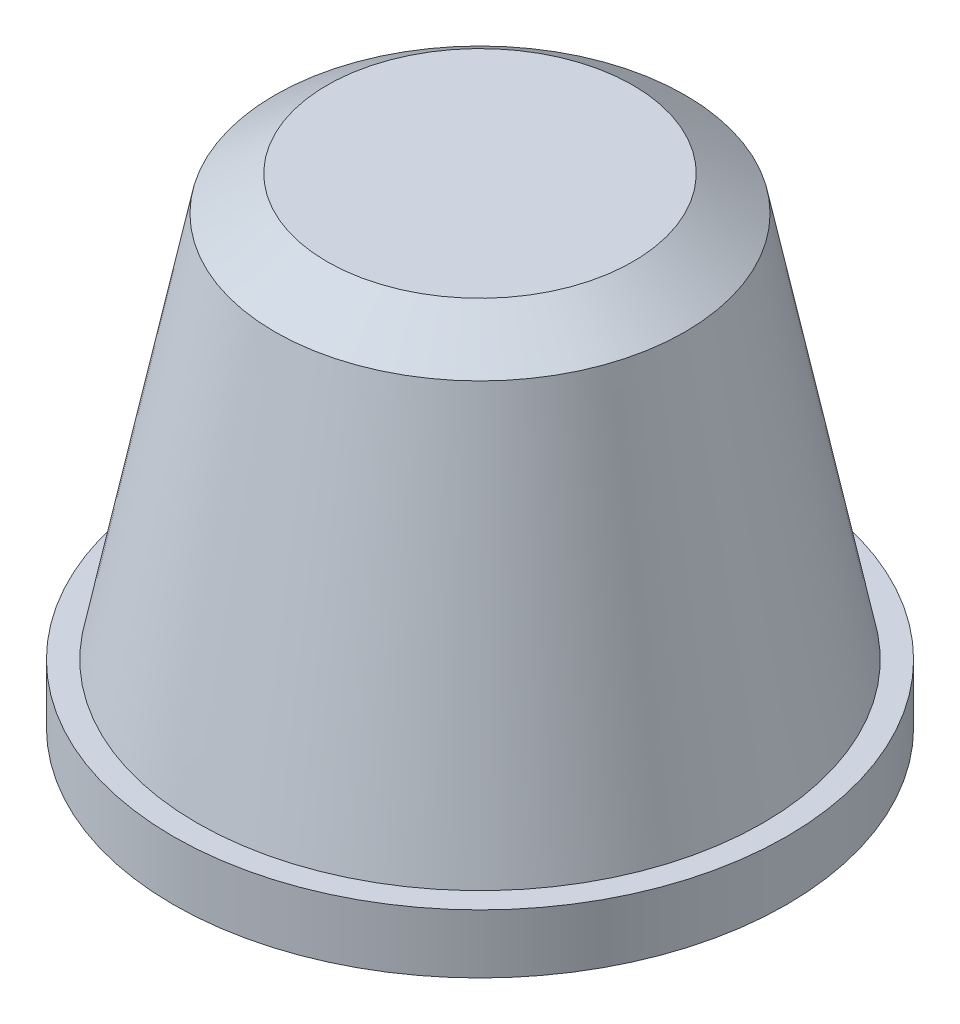
SolidWorks part; units mm, degrees
material "PET"
ref_plane "Front Plane" through (0, 0, 0) normal (0, 0, 1) x (1, 0, 0)
ref_plane "Top Plane" through (0, 0, 0) normal (0, 1, 0) x (1, 0, 0)
ref_plane "Right Plane" through (0, 0, 0) normal (1, 0, 0) x (0, 0, -1)
sketch "Sketch3" plane through (0, 0, 0) normal (0, 0, 1) x (1, 0, 0)
  line L0 (-6.858, -0.3614) -> (-32.858, -0.3614)
  line L1 (-32.858, -0.3614) -> (-32.858, 4.6386)
  line L2 (-32.858, 4.6386) -> (-30.858, 4.6386)
  line L3 (-30.858, 4.6386) -> (-25.0106, 33.6386)
  line L4 (-6.858, 40.3397) -> (-6.858, -0.3614)
  line L5 (-25.0106, 33.6386) -> (-23.6595, 40.3397)
  line L6 (-23.6595, 40.3397) -> (-6.858, 40.3397)
  dimension "D2" = 5
  dimension "D3" = 2
  dimension "D4" = 29
revolve "Revolve1" add sketch "Sketch3" angle 360 about L4
chamfer "Chamfer1" distance 3 angle 45 1 edges at (-6.858, 40.3397, 16.8014)
